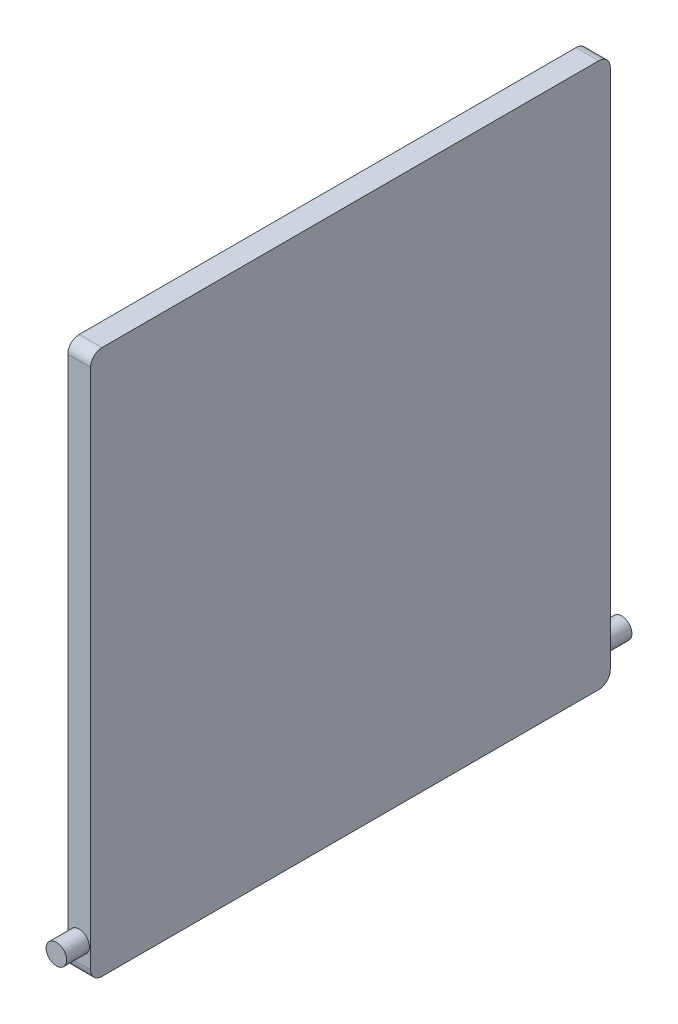
SolidWorks part; units mm, degrees
ref_plane "Front Plane" through (0, 0, 0) normal (0, 0, 1) x (1, 0, 0)
ref_plane "Top Plane" through (0, 0, 0) normal (0, 1, 0) x (1, 0, 0)
ref_plane "Right Plane" through (0, 0, 0) normal (1, 0, 0) x (0, 0, -1)
sketch "Sketch1" plane through (0, 0, 0) normal (1, 0, 0) x (0, 0, -1)
  line L1 (-114, 0) -> (114, 0)
  line L2 (-114, 0) -> (-114, 238.92)
  line L3 (-114, 238.92) -> (114, 238.92)
  line L4 (114, 0) -> (114, 238.92)
  dimension "D1" = 228
  dimension "D2" = 238.92
extrude "Boss-Extrude1" add sketch "Sketch1" against normal blind 10
sketch "Sketch2" plane through (0, 0, -114) normal (0, 0, -1) x (-1, 0, 0)
  line L0 (10, 0) -> (0, 0) construction
  line L1 (5, 0) -> (5, 13.5) construction
  circle A0 centre (5, 13.5) radius 4.5
  dimension "D1" = 9
  dimension "D2" = 13.5
extrude "Boss-Extrude2" add sketch "Sketch2" along normal blind 10
mirror "Mirror1" about plane through (0, 0, 0) normal (0, 0, 1) of "Boss-Extrude2"
fillet "Fillet1" radius 5 4 edges at (-5, 0, -114) (-5, 0, 114) (-5, 238.92, -114) (-5, 238.92, 114)
